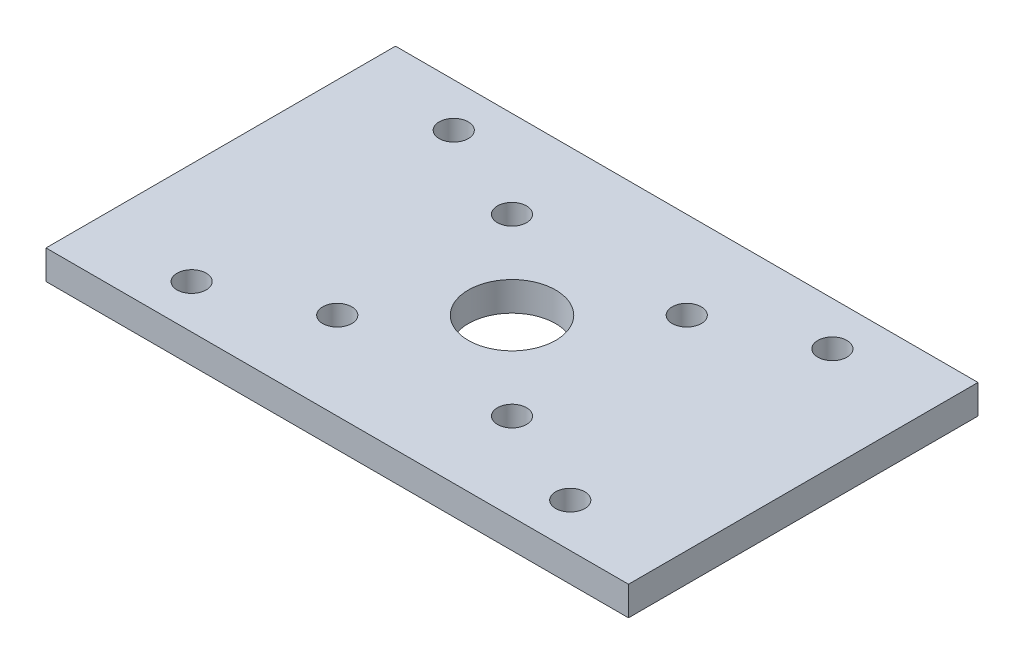
SolidWorks part; units mm, degrees
material "6061-T6 (SS)"
ref_plane "Front Plane" through (0, 0, 0) normal (0, 0, 1) x (1, 0, 0)
ref_plane "Top Plane" through (0, 0, 0) normal (0, 1, 0) x (1, 0, 0)
ref_plane "Right Plane" through (0, 0, 0) normal (1, 0, 0) x (0, 0, -1)
sketch "Sketch1" plane through (0, 0, 0) normal (0, 1, 0) x (1, 0, 0)
  line L1 (-63.5, -38.1) -> (63.5, -38.1)
  line L2 (-63.5, -38.1) -> (-63.5, 38.1)
  line L3 (-63.5, 38.1) -> (63.5, 38.1)
  line L4 (63.5, -38.1) -> (63.5, 38.1)
  line L5 (-63.5, -38.1) -> (63.5, 38.1) construction
  line L6 (-63.5, 38.1) -> (63.5, -38.1) construction
  point P0 (0, 0)
  dimension "D1" = 76.2
  dimension "D2" = 127
extrude "Boss-Extrude1" add sketch "Sketch1" along normal blind 6.35
sketch "Sketch2" plane through (0, 6.35, 0) normal (0, 1, 0) x (1, 0, 0)
  line L1 (-41.275, -28.575) -> (41.275, -28.575) construction
  line L2 (-41.275, -28.575) -> (-41.275, 28.575) construction
  line L3 (-41.275, 28.575) -> (41.275, 28.575) construction
  line L4 (41.275, -28.575) -> (41.275, 28.575) construction
  line L5 (-41.275, -28.575) -> (41.275, 28.575) construction
  line L6 (-41.275, 28.575) -> (41.275, -28.575) construction
  line L7 (-19.05, -19.05) -> (19.05, -19.05) construction
  line L8 (-19.05, -19.05) -> (-19.05, 19.05) construction
  line L9 (-19.05, 19.05) -> (19.05, 19.05) construction
  line L10 (19.05, -19.05) -> (19.05, 19.05) construction
  line L11 (-19.05, -19.05) -> (19.05, 19.05) construction
  line L12 (-19.05, 19.05) -> (19.05, -19.05) construction
  circle A0 centre (-41.275, 28.575) radius 3.175
  circle A1 centre (41.275, 28.575) radius 3.175
  circle A2 centre (41.275, -28.575) radius 3.175
  circle A3 centre (-41.275, -28.575) radius 3.175
  circle A4 centre (-19.05, 19.05) radius 3.175
  circle A5 centre (19.05, 19.05) radius 3.175
  circle A6 centre (19.05, -19.05) radius 3.175
  circle A7 centre (-19.05, -19.05) radius 3.175
  circle A8 centre (0, 0) radius 9.525
  point P0 (0, 0)
  point P10 (0, 0)
  dimension "D3" = 6.35
  dimension "D6" = 6.35
  dimension "D7" = 19.05
  dimension "D1" = 82.55
  dimension "D2" = 57.15
  dimension "D4" = 38.1
  dimension "D5" = 38.1
extrude "Cut-Extrude1" cut sketch "Sketch2" against normal through all
